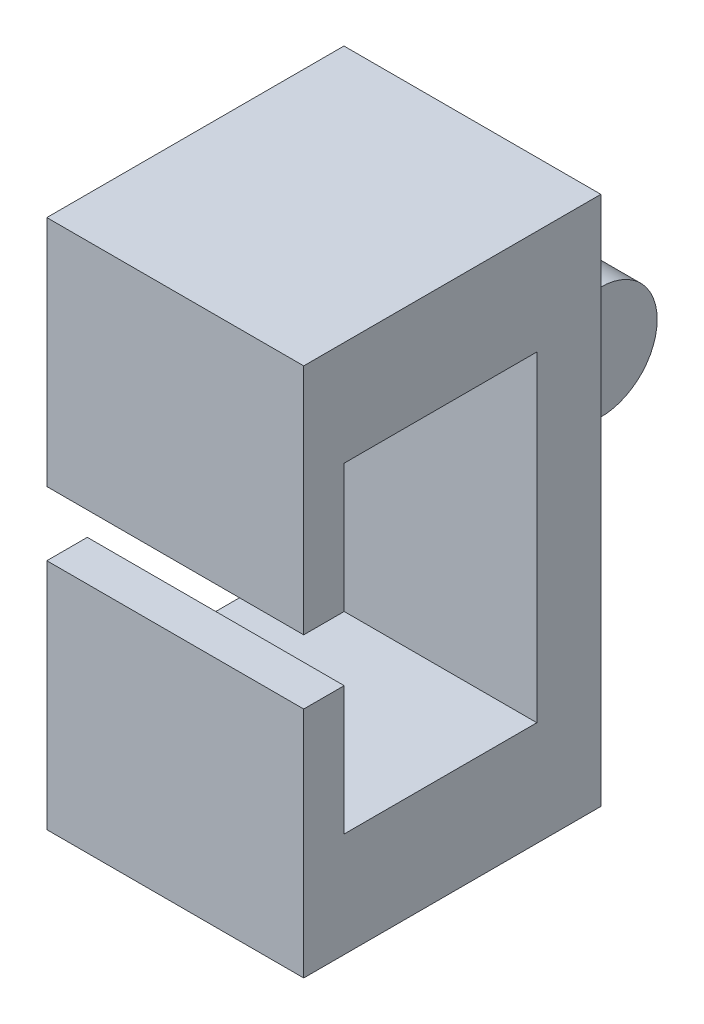
SolidWorks part; units mm, degrees
ref_plane "Front Plane" through (0, 0, 0) normal (1, 0, 0) x (0, 1, 0)
ref_plane "Top Plane" through (0, 0, 0) normal (0, 0, 1) x (0, 1, 0)
ref_plane "Right Plane" through (0, 0, 0) normal (0, 1, 0) x (-1, 0, 0)
sketch "Sketch1" plane through (0, 0, 0) normal (1, 0, 0) x (0, 1, 0)
  circle A0 centre (0, 0) radius 11.1361
  dimension "D1" = 22.2722
extrude "Boss-Extrude1" add sketch "Sketch1" along normal blind 25.4 contours A0
sketch "Sketch2" plane through (0, 0, 0) normal (-1, 0, 0) x (0, -1, 0)
  line L0 (12.2497, 0) -> (-12.2497, 0) construction
  line L1 (-11.1361, 0) -> (11.1252, 0)
  line L2 (-11.1361, 0) -> (-11.1361, 25.4)
  line L3 (-11.1361, 25.4) -> (11.1252, 25.4)
  line L4 (11.1252, 0) -> (11.1252, 25.4)
  circle A0 centre (0, 0) radius 11.1361 construction
  point P8 (-11.1252, 25.4)
  dimension "D1" = 25.4
extrude "Boss-Extrude2" add sketch "Sketch2" against normal blind 3.8346 contours L2 L3 L4 L1
sketch "Sketch3" plane through (0, 0, 0) normal (1, 0, 0) x (0, 1, 0)
  line L0 (0, -13.97) -> (0, 13.97) construction
  line L1 (-31.75, 25.4) -> (31.75, 25.4)
  line L2 (-31.75, 25.4) -> (-31.75, 38.0545)
  line L3 (-31.75, 38.0545) -> (31.75, 38.0545)
  line L4 (31.75, 25.4) -> (31.75, 38.0545)
  line L5 (11.1361, 25.4) -> (-11.1252, 25.4) construction
  point P4 (0, 25.4)
  dimension "D1" = 63.5
  dimension "D2" = 12.6545
extrude "Boss-Extrude3" add sketch "Sketch3" along normal blind 50.8
sketch "Sketch4" plane through (0, 0, 0) normal (1, 0, 0) x (0, 1, 0)
  line L0 (31.75, 38.0545) -> (-31.75, 38.0545) construction
  line L1 (-31.75, 25.4) -> (-52.4147, 25.4)
  line L2 (-31.75, 25.4) -> (-31.75, 76.1545)
  line L3 (-31.75, 76.1545) -> (-52.4147, 76.1545)
  line L4 (-52.4147, 25.4) -> (-52.4147, 76.1545)
  line L5 (31.75, 25.4) -> (52.4147, 25.4)
  line L6 (31.75, 25.4) -> (31.75, 76.1545)
  line L7 (31.75, 76.1545) -> (52.4147, 76.1545)
  line L8 (52.4147, 25.4) -> (52.4147, 76.1545)
  point P10 (38.6155, 72.7258)
  dimension "D1" = 20.6647
  dimension "D2" = 38.1
extrude "Boss-Extrude4" add sketch "Sketch4" along normal blind 50.8
sketch "Sketch5" plane through (0, 0, 0) normal (1, 0, 0) x (0, 1, 0)
  line L1 (-52.4147, 76.1545) -> (-6.35, 76.1545)
  line L2 (-52.4147, 76.1545) -> (-52.4147, 84.1579)
  line L3 (-52.4147, 84.1579) -> (-6.35, 84.1579)
  line L4 (-6.35, 76.1545) -> (-6.35, 84.1579)
  line L5 (52.4147, 76.1545) -> (6.35, 76.1545)
  line L6 (52.4147, 76.1545) -> (52.4147, 84.1579)
  line L7 (52.4147, 84.1579) -> (6.35, 84.1579)
  line L8 (6.35, 76.1545) -> (6.35, 84.1579)
  point P10 (0, 0)
  point P12 (0, 0)
  point P13 (0, 0)
  point P14 (0, 0)
  dimension "D1" = 8.0034
  dimension "D2" = 25.4
  dimension "D3" = 12.7
extrude "Boss-Extrude5" add sketch "Sketch5" along normal blind 50.8
equation "\"SAFETY_FAC\"= 4'Given Safety Factor"
equation "\"LOAD\"= 600'Chosen Applied Load (lbf)"
equation "\"LENGTH_A\"= 1in'Chosen Length for Feature A (in)"
equation "\"STRENGTH\"= 36259.4'ASTM A36 Steel Yield Strenght (psi)"
equation "\"DIAMETER_A\"= 2 * ( ( 4 * \"SAFETY_FAC\" * \"LOAD\" * \"LENGTH_A\" ) / ( PI * \"STRENGTH\" ) ) ^ ( 1 / 3 )'Calculated Diameter of Feature A (in)"
equation "\"THICKNESS_B\"= ( \"LOAD\" * 8 ) / ( \"STRENGTH\" * \"DIAMETER_A\" )'Calculated Thickness of Feature B (in)"
equation "\"LENGTH_C\"= 2.5'Found Length based on Given Rigid T-beam Dimensions (in)"
equation "\"PRIMARY_THICKNESS\"= 2'Chosen Thickness of the primary section (in_"
equation "\"HEIGHT_C\"= ( ( 3 * \"LOAD\" * \"LENGTH_C\" * \"SAFETY_FAC\" ) / ( \"PRIMARY_THICKNESS\" * \"STRENGTH\" ) ) ^ ( 1 / 2 )'Calculated Height of Feature C (in)"
equation "\"LOAD_DISTANCE_D\"= \"LENGTH_C\" / 2'Calculated Distance of Load Applied to Feature D (in)"
equation "\"HEIGHT_D\"= 1.5'Found Height based on the GIven Rigid T-beam Dimensions (in)"
equation "\"LENGTH_D\"= ( ( 12 * \"LOAD\" * \"LOAD_DISTANCE_D\" * \"SAFETY_FAC\" ) / ( \"HEIGHT_D\" * \"STRENGTH\" ) ) ^ ( 1 / 2 )'Calculated Length of Feature D (in)"
equation "\"LENGTH_E\"= 1'Found Length for Feature E on given Rigid T-Beam Dimensions (in)"
equation "\"HEIGHT_E\"= ( ( 3 * \"LENGTH_E\" * \"LOAD\" * \"SAFETY_FAC\" ) / ( \"PRIMARY_THICKNESS\" * \"STRENGTH\" ) ) ^ ( 1 / 2 )'Calculated height of Feature E (in)"
equation "\"D1@Sketch1\"=\"DIAMETER_A\""
equation "\"D1@Boss-Extrude1\"=\"LENGTH_A\""
equation "\"D1@Boss-Extrude2\"=\"THICKNESS_B\""
equation "\"D1@Sketch3\"=\"LENGTH_C\""
equation "\"D2@Sketch3\"=\"HEIGHT_C\""
equation "\"D1@Boss-Extrude3\"=\"PRIMARY_THICKNESS\""
equation "\"D2@Sketch4\"=\"HEIGHT_D\""
equation "\"D1@Sketch4\"=\"LENGTH_D\""
equation "\"D1@Boss-Extrude4\"=\"PRIMARY_THICKNESS\""
equation "\"D1@Sketch5\"=\"HEIGHT_E\""
equation "\"D2@Sketch5\"=\"LENGTH_E\""
equation "\"D1@Boss-Extrude5\"=\"PRIMARY_THICKNESS\""
